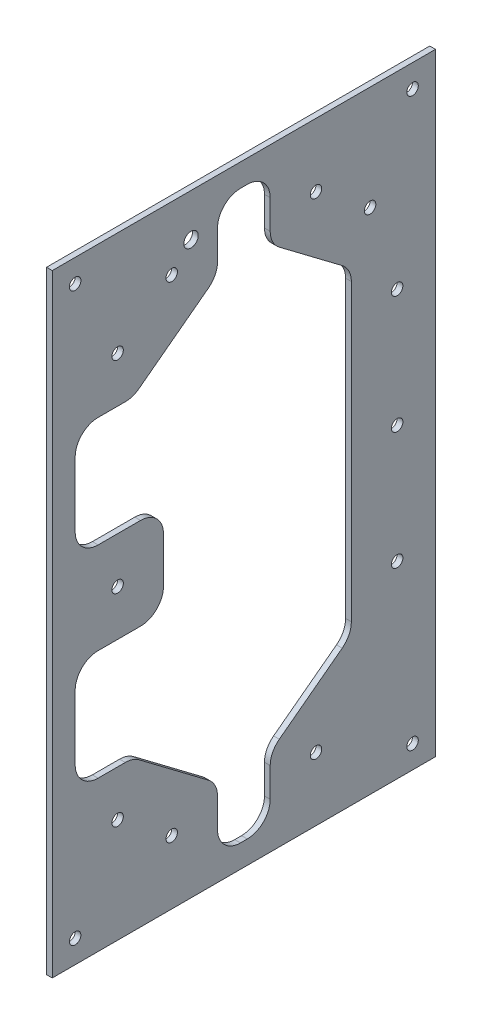
SolidWorks part; units mm, degrees
material "6061-T6 (SS)"
ref_plane "Front Plane" through (0, 0, 0) normal (0, 0, 1) x (1, 0, 0)
ref_plane "Top Plane" through (0, 0, 0) normal (0, 1, 0) x (1, 0, 0)
ref_plane "Right Plane" through (0, 0, 0) normal (1, 0, 0) x (0, 0, -1)
sketch "Sketch1" plane through (0, 0, 0) normal (1, 0, 0) x (0, 0, -1)
  line L0 (0, -169.8625) -> (212.5, -169.8625) construction
  line L1 (0, 0) -> (212.5, 0)
  line L2 (0, 0) -> (0, -339.725)
  line L3 (0, -339.725) -> (212.5, -339.725)
  line L4 (212.5, 0) -> (212.5, -339.725)
  line L5 (153.5, -35.2425) -> (59, -35.2425) construction
  line L6 (191.25, -104.5325) -> (191.25, -169.8625) construction
  line L7 (13.5, -50.2425) -> (59, -50.2425) construction
  line L8 (36.25, -50.2425) -> (36.25, -169.8625) construction
  line L9 (106.25, 0) -> (106.25, -339.725) construction
  line L10 (173.5, -104.5325) -> (191.25, -104.5325) construction
  circle A0 centre (12.7, -12.7) radius 3.175
  circle A1 centre (199.8, -12.7) radius 3.175
  circle A2 centre (66.25, -35.2425) radius 3.175
  circle A3 centre (146.25, -35.2425) radius 3.175
  circle A4 centre (176.25, -57.8625) radius 3.175
  circle A5 centre (36.25, -57.8625) radius 3.175
  circle A6 centre (191.25, -104.5325) radius 3.175
  circle A7 centre (36.25, -169.8625) radius 3.175
  circle A8 centre (191.25, -169.8625) radius 3.175
  circle A9 centre (36.25, -281.8625) radius 3.175
  circle A10 centre (66.25, -304.4825) radius 3.175
  circle A11 centre (12.7, -327.025) radius 3.175
  circle A12 centre (199.8, -327.025) radius 3.175
  circle A13 centre (146.25, -304.4825) radius 3.175
  circle A14 centre (191.25, -235.1925) radius 3.175
  dimension "D1" = 339.725
  dimension "D2" = 212.5
  dimension "D3" = 40
  dimension "D4" = 112
  dimension "D5" = 85
  dimension "D6" = 157.1625
extrude "Boss-Extrude1" add sketch "Sketch1" along normal blind 3.175
sketch "Sketch2" plane through (3.175, 0, 0) normal (1, 0, 0) x (0, 0, -1)
  line L1 (165.85, -88.1617) -> (165.85, -251.5633)
  line L4 (0, 0) -> (0, -339.725)
  line L5 (0, -339.725) -> (212.5, -339.725)
  line L6 (212.5, -339.725) -> (212.5, 0)
  line L7 (212.5, 0) -> (0, 0)
  line L8 (0, 0) -> (0, -339.725)
  line L9 (0, -339.725) -> (212.5, -339.725)
  line L10 (212.5, -339.725) -> (212.5, 0)
  line L11 (212.5, 0) -> (0, 0)
  line L14 (25.4, -144.4625) -> (48.95, -144.4625)
  line L15 (25.4, -83.2625) -> (40.5014, -83.2625)
  line L16 (12.7, -95.9625) -> (12.7, -131.7625)
  line L17 (34.7163, -60.6425) -> (37.7837, -60.6425)
  line L18 (61.65, -70.5625) -> (61.65, -70.522)
  line L19 (61.65, -182.5625) -> (61.65, -157.1625)
  line L20 (36.25, -57.8625) -> (66.25, -35.2425) construction
  line L21 (48.1473, -80.703) -> (86.5959, -51.7127)
  line L22 (91.65, -25.4) -> (91.65, -41.5722)
  line L23 (120.85, -25.4) -> (120.85, -41.5722)
  line L24 (104.35, -12.7) -> (108.15, -12.7)
  line L25 (176.25, -57.8625) -> (146.25, -35.2425) construction
  line L26 (125.9041, -51.7127) -> (160.7959, -78.0212)
  line L27 (0, -169.8625) -> (212.5, -169.8625) construction
  line L28 (176.25, -281.8625) -> (146.25, -304.4825) construction
  line L29 (36.25, -281.8625) -> (66.25, -304.4825) construction
  line L30 (125.9041, -288.0123) -> (160.7959, -261.7038)
  line L31 (104.35, -327.025) -> (108.15, -327.025)
  line L32 (120.85, -314.325) -> (120.85, -298.1528)
  line L33 (91.65, -314.325) -> (91.65, -298.1528)
  line L34 (48.1473, -259.022) -> (86.5959, -288.0123)
  line L35 (61.65, -269.1625) -> (61.65, -269.203)
  line L36 (34.7163, -279.0825) -> (37.7837, -279.0825)
  line L37 (12.7, -243.7625) -> (12.7, -207.9625)
  line L38 (25.4, -256.4625) -> (40.5014, -256.4625)
  line L39 (25.4, -195.2625) -> (48.95, -195.2625)
  circle A0 centre (176.25, -57.8625) radius 3.175 construction
  circle A1 centre (146.25, -35.2425) radius 3.175 construction
  circle A2 centre (66.25, -35.2425) radius 3.175 construction
  circle A3 centre (36.25, -57.8625) radius 3.175 construction
  circle A4 centre (36.25, -169.8625) radius 3.175 construction
  circle A5 centre (36.25, -281.8625) radius 3.175 construction
  circle A6 centre (66.25, -304.4825) radius 3.175 construction
  circle A7 centre (146.25, -304.4825) radius 3.175 construction
  circle A8 centre (191.25, -235.1925) radius 3.175 construction
  circle A9 centre (191.25, -169.8625) radius 3.175 construction
  circle A10 centre (191.25, -104.5325) radius 3.175 construction
  circle A11 centre (176.25, -57.8625) radius 3.175 construction
  circle A12 centre (146.25, -35.2425) radius 3.175 construction
  circle A13 centre (66.25, -35.2425) radius 3.175 construction
  circle A14 centre (36.25, -57.8625) radius 3.175 construction
  circle A15 centre (36.25, -169.8625) radius 3.175 construction
  circle A16 centre (36.25, -281.8625) radius 3.175 construction
  circle A17 centre (66.25, -304.4825) radius 3.175 construction
  circle A18 centre (146.25, -304.4825) radius 3.175 construction
  circle A19 centre (191.25, -235.1925) radius 3.175 construction
  circle A20 centre (191.25, -169.8625) radius 3.175 construction
  circle A21 centre (191.25, -104.5325) radius 3.175 construction
  arc A28 (48.95, -144.4625) -> (61.65, -157.1625) centre (48.95, -157.1625) cw
  arc A29 (12.7, -131.7625) -> (25.4, -144.4625) centre (25.4, -131.7625) ccw
  arc A30 (12.7, -95.9625) -> (25.4, -83.2625) centre (25.4, -95.9625) cw
  arc A33 (165.85, -88.1617) -> (160.7959, -78.0212) centre (153.15, -88.1617) ccw
  arc A34 (125.9041, -51.7127) -> (120.85, -41.5722) centre (133.55, -41.5722) cw
  arc A35 (108.15, -12.7) -> (120.85, -25.4) centre (108.15, -25.4) cw
  arc A36 (104.35, -12.7) -> (91.65, -25.4) centre (104.35, -25.4) ccw
  arc A37 (86.5959, -51.7127) -> (91.65, -41.5722) centre (78.95, -41.5722) ccw
  arc A38 (48.1473, -80.703) -> (40.5014, -83.2625) centre (40.5014, -70.5625) cw
  circle A39 centre (36.25, -281.8625) radius 3.175 construction
  circle A40 centre (66.25, -304.4825) radius 3.175 construction
  circle A41 centre (146.25, -304.4825) radius 3.175 construction
  circle A42 centre (176.25, -281.8625) radius 3.175 construction
  arc A43 (48.1473, -259.022) -> (40.5014, -256.4625) centre (40.5014, -269.1625) ccw
  arc A44 (86.5959, -288.0123) -> (91.65, -298.1528) centre (78.95, -298.1528) cw
  arc A45 (104.35, -327.025) -> (91.65, -314.325) centre (104.35, -314.325) cw
  arc A46 (108.15, -327.025) -> (120.85, -314.325) centre (108.15, -314.325) ccw
  arc A47 (125.9041, -288.0123) -> (120.85, -298.1528) centre (133.55, -298.1528) ccw
  arc A48 (165.85, -251.5633) -> (160.7959, -261.7038) centre (153.15, -251.5633) cw
  arc A49 (12.7, -243.7625) -> (25.4, -256.4625) centre (25.4, -243.7625) ccw
  arc A50 (12.7, -207.9625) -> (25.4, -195.2625) centre (25.4, -207.9625) cw
  arc A51 (48.95, -195.2625) -> (61.65, -182.5625) centre (48.95, -182.5625) ccw
  point P73 (61.65, -83.2625)
  point P78 (61.65, -60.6425)
  point P92 (61.65, -279.0825)
  point P110 (61.65, -169.8625)
  point P114 (165.85, -169.8625)
  point P115 (61.65, -256.4625)
  dimension "D11" = 25.4
  dimension "D13" = 25.4
  dimension "D17" = 12.7
  dimension "D2" = 25.4
  dimension "D7" = 25.4
  dimension "D8" = 25.4
  dimension "D9" = 25.4
  dimension "D14" = 25.4
  dimension "D15" = 12.7
  dimension "D16" = 25.4
  dimension "D1" = 0
extrude "Cut-Extrude1" cut sketch "Sketch2" against normal through all
sketch "Sketch3" plane through (0, 0, 0) normal (-1, 0, 0) x (0, 0, 1)
  line L0 (-346.3782, 40.5874) -> (-378.5247, -326.307) construction
  line L1 (-346.3782, 40.5874) -> (-378.5247, -326.307)
  line L3 (-580.9492, -308.571) -> (-378.5247, -326.307) construction
  circle A0 centre (-353.3431, -302.4137) radius 4
  dimension "D2" = 26
  dimension "D3" = 8
  dimension "D1" = 23
extrude "Cut-Extrude2" cut sketch "Sketch3" against normal blind 45.72 contours A0
sketch "Sketch4" plane through (0, 0, 0) normal (-1, 0, 0) x (0, 0, 1)
  circle A0 centre (-76.9625, -23.6135) radius 4 construction
  circle A1 centre (-76.9625, -23.6135) radius 4
extrude "Cut-Extrude3" cut sketch "Sketch4" against normal blind 14.986
